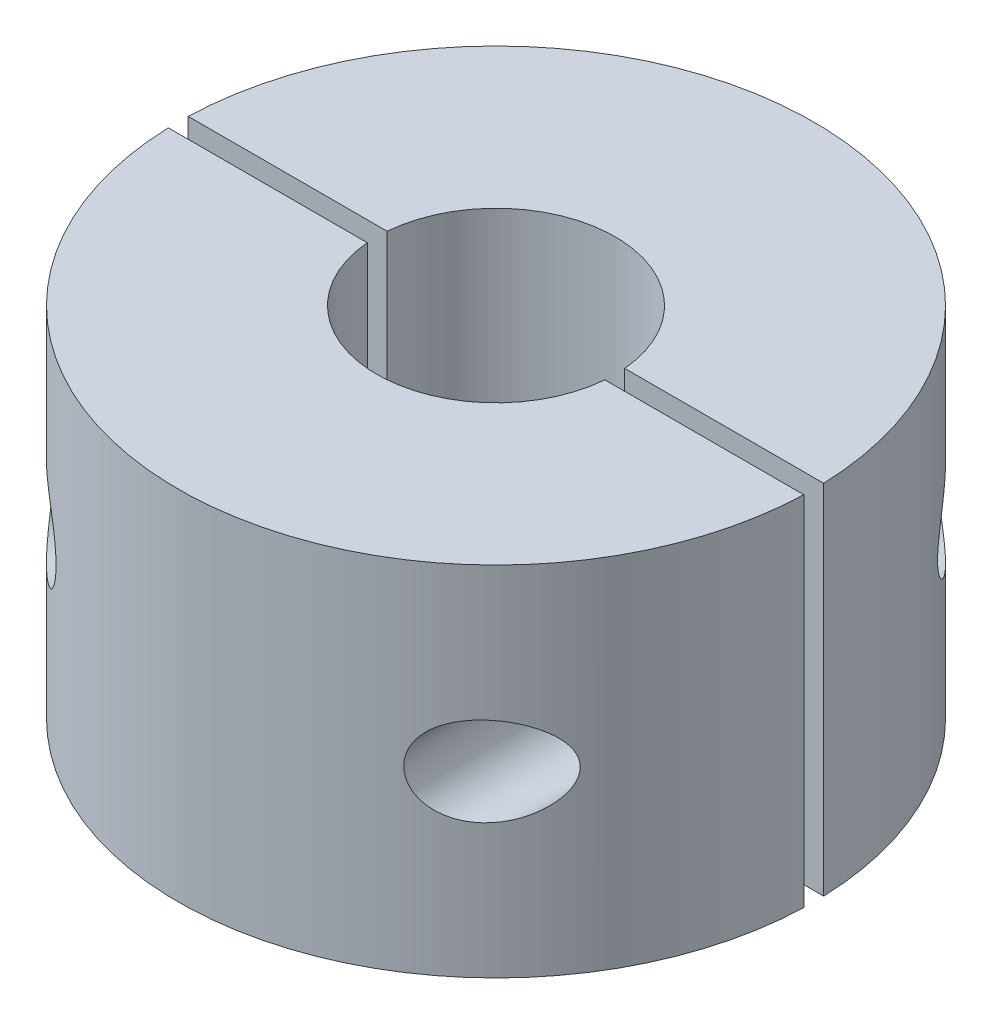
SolidWorks part; units mm, degrees
ref_plane "前视基准面" through (0, 0, 0) normal (0, 0, 1) x (1, 0, 0)
ref_plane "上视基准面" through (0, 0, 0) normal (0, 1, 0) x (1, 0, 0)
ref_plane "右视基准面" through (0, 0, 0) normal (1, 0, 0) x (0, 0, -1)
other "Configuration Table"
sketch "草图1" plane through (0, 0, 0) normal (0, 1, 0) x (1, 0, 0)
  circle A0 centre (0, 0) radius 8
  dimension "D1" = 16
extrude "凸台-拉伸1" add sketch "草图1" along normal blind 9
sketch "草图3" plane through (0, 9, 0) normal (0, 1, 0) x (1, 0, 0)
  circle A1 centre (0, 0) radius 3
  dimension "D1" = 6
extrude "切除-拉伸2" cut sketch "草图3" against normal through all
sketch "草图5" plane through (0, 9, 0) normal (0, 1, 0) x (1, 0, 0)
  line L1 (-10, -0.25) -> (10, -0.25)
  line L2 (-10, -0.25) -> (-10, 0.25)
  line L3 (-10, 0.25) -> (10, 0.25)
  line L4 (10, -0.25) -> (10, 0.25)
  line L5 (-10, -0.25) -> (10, 0.25) construction
  line L6 (-10, 0.25) -> (10, -0.25) construction
  point P0 (0, 0)
  dimension "D1" = 0.5
  dimension "D2" = 20
extrude "切除-拉伸4" cut sketch "草图5" against normal through all
sketch "草图6" plane through (0, 0, 0) normal (0, 0, 1) x (1, 0, 0)
  line L0 (7.9961, 9) -> (7.9961, 0) construction
  line L1 (7.9961, 9) -> (-7.9961, 9) construction
  line L2 (0, -55) -> (0, 55) construction
  circle A0 centre (5.4961, 4.5) radius 1.1202
  circle A1 centre (-5.4961, 4.5) radius 1.1202
  dimension "D1" = 2.5
  dimension "D2" = 4.5
extrude "切除-拉伸5" cut sketch "草图6" against normal through all and the other way through all
